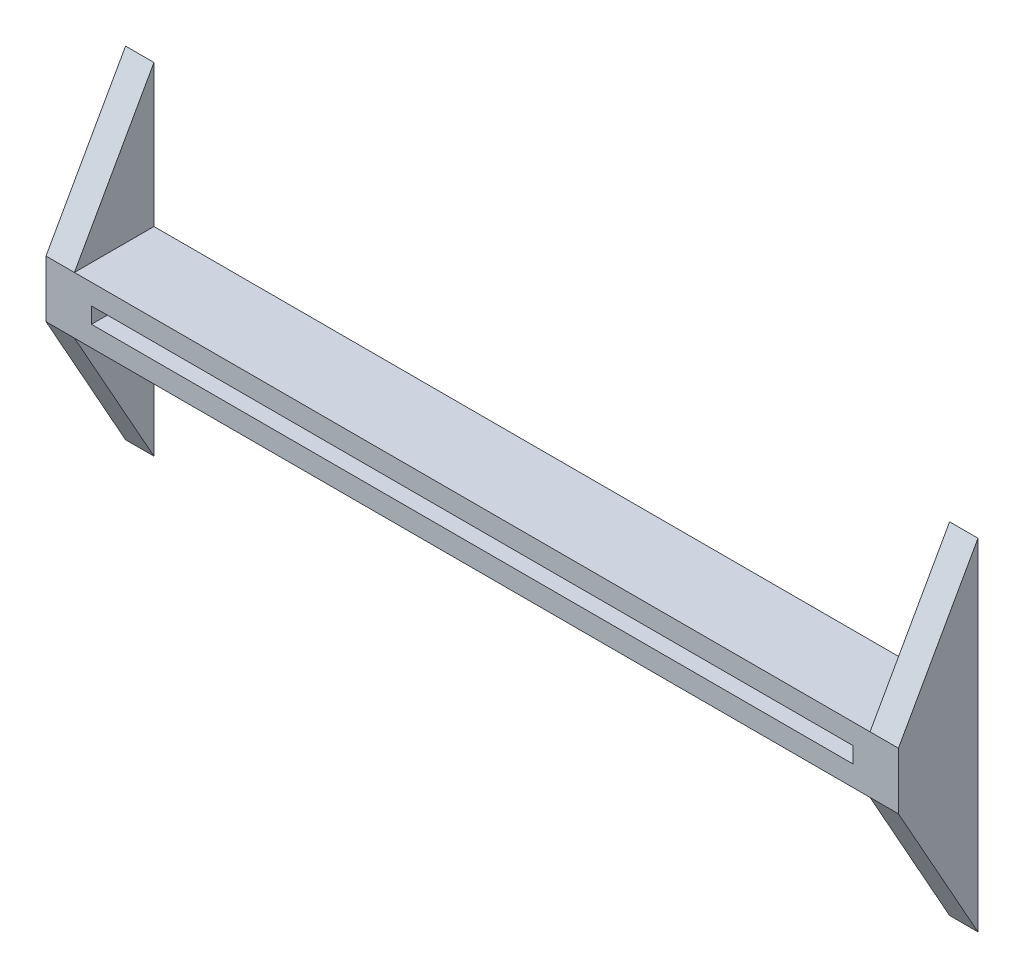
SolidWorks part; units mm, degrees
ref_plane "Front Plane" through (0, 0, 0) normal (0, 0, 1) x (1, 0, 0)
ref_plane "Top Plane" through (0, 0, 0) normal (0, 1, 0) x (1, 0, 0)
ref_plane "Right Plane" through (0, 0, 0) normal (1, 0, 0) x (0, 0, -1)
sketch "Sketch1" plane through (0, 0, 0) normal (0, 0, 1) x (1, 0, 0)
  line L1 (35, 2.5) -> (-35, 2.5)
  line L2 (35, 2.5) -> (35, -2.5)
  line L3 (35, -2.5) -> (-35, -2.5)
  line L4 (-35, 2.5) -> (-35, -2.5)
  line L5 (35, 2.5) -> (-35, -2.5) construction
  line L6 (35, -2.5) -> (-35, 2.5) construction
  line L7 (33.5, 0.7) -> (-33.5, 0.7)
  line L8 (33.5, 0.7) -> (33.5, -0.7)
  line L9 (33.5, -0.7) -> (-33.5, -0.7)
  line L10 (-33.5, 0.7) -> (-33.5, -0.7)
  line L11 (33.5, 0.7) -> (-33.5, -0.7) construction
  line L12 (33.5, -0.7) -> (-33.5, 0.7) construction
  point P0 (0, 0)
  point P6 (0, 0)
  dimension "D1" = 70
  dimension "D2" = 5
  dimension "D3" = 67
  dimension "D4" = 1.4
extrude "Boss-Extrude1" add sketch "Sketch1" along normal blind 5
sketch "Sketch2" plane through (0, 0, 0) normal (0, 0, -1) x (-1, 0, 0)
  line L1 (-35, 2.5) -> (35, 2.5)
  line L2 (-35, 2.5) -> (-35, -2.5)
  line L3 (-35, -2.5) -> (35, -2.5)
  line L4 (35, 2.5) -> (35, -2.5)
extrude "Boss-Extrude2" add sketch "Sketch2" along normal blind 2 contours L2 L1 L4 L3
sketch "Sketch3" plane through (35, 0, 0) normal (1, 0, 0) x (0, 0, -1)
  line L0 (-5, 2.5) -> (2, 15)
  line L1 (2, 15) -> (2, -15)
  line L2 (2, -15) -> (-5, -2.5)
  line L3 (-5, -2.5) -> (-5, 2.5)
  line L4 (2, 2.5) -> (2, -2.5) construction
  point P4 (2, 0)
  point P9 (2, 0)
  dimension "D1" = 30
extrude "Boss-Extrude3" add sketch "Sketch3" along normal blind 2.5
sketch "Sketch4" plane through (-35, 0, 0) normal (-1, 0, 0) x (0, 0, 1)
  line L0 (5, 2.5) -> (-2, 15)
  line L1 (-2, 15) -> (-2, -15)
  line L2 (-2, -15) -> (5, -2.5)
  line L3 (5, -2.5) -> (5, 2.5)
  line L4 (-2, 2.5) -> (-2, -2.5) construction
  point P6 (-2, 0)
  point P9 (-2, 0)
  point P10 (1.1768, 10.2022)
  dimension "D1" = 30
extrude "Boss-Extrude4" add sketch "Sketch4" along normal blind 2.5
